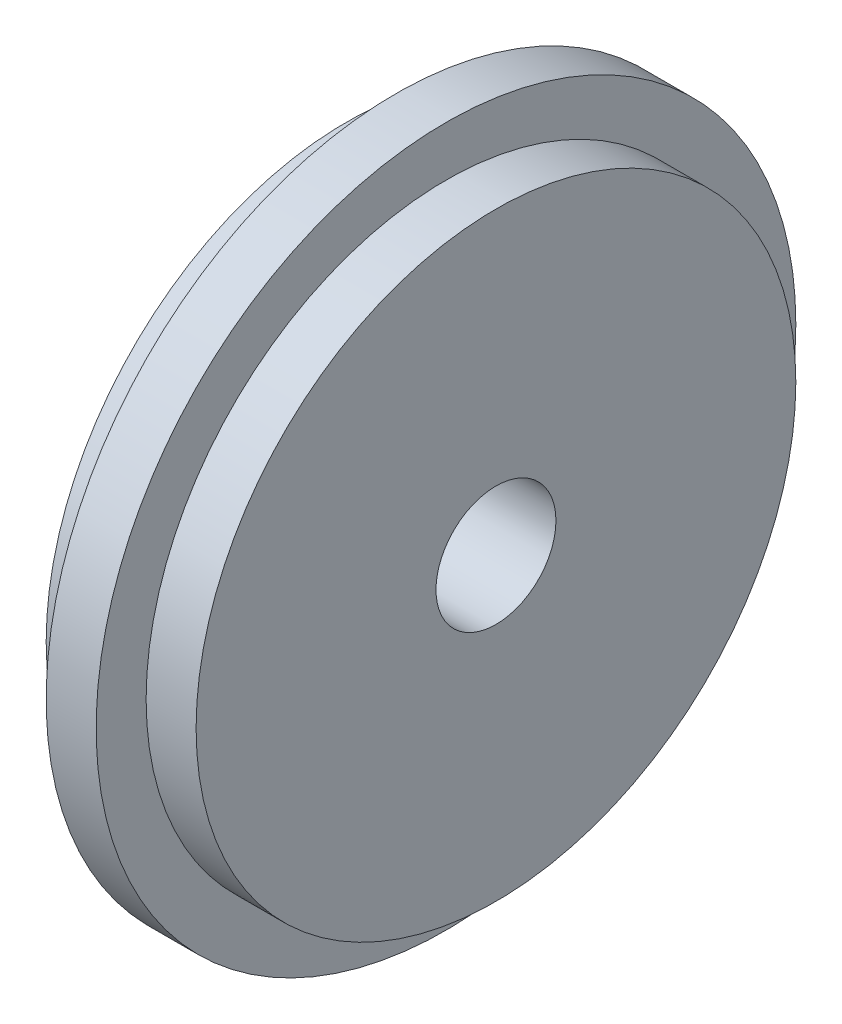
SolidWorks part; units mm, degrees
material "Náilon 6/10"
ref_plane "Plano frontal" through (0, 0, 0) normal (0, 0, 1) x (1, 0, 0)
ref_plane "Plano superior" through (0, 0, 0) normal (0, 1, 0) x (1, 0, 0)
ref_plane "Plano direito" through (0, 0, 0) normal (1, 0, 0) x (0, 0, -1)
sketch "Sketch1" plane through (0, 0, 0) normal (1, 0, 0) x (0, 0, -1)
  circle A0 centre (0, 0) radius 30
  dimension "D1" = 60
extrude "Corpo da Roda" add sketch "Sketch1" along normal mid plane 15
sketch "Sketch8" plane through (0, 0, 0) normal (1, 0, 0) x (0, 0, -1)
  circle A0 centre (0, 0) radius 35
  circle A1 centre (0, 0) radius 30 construction
  dimension "D1" = 5
extrude "Boss-Extrude2" add sketch "Sketch8" along normal mid plane 5
hole_wizard "Furo do Hub (mesmo diâmetro) - Ø1.0 (1) Diameter Hole1" positions "Sketch5" profile "Sketch4" hole size "Ø12.0" standard "DIN" end condition through all
sketch "Sketch5" plane through (7.5, 0, 0) normal (1, 0, 0) x (0, 0, -1)
  point P0 (0, 0)
sketch "Sketch4" plane through (7.5, 0, 0) normal (0, 1, 0) x (0, 0, -1)
  line L0 (0, 0) -> (0, 15)
  line L1 (0, 15) -> (6, 15)
  line L2 (6, 15) -> (6, 0)
  line L5 (6, 0) -> (0, 0)
  line L11 (0, -6.35) -> (0, 107.95) construction
  dimension "Thru Hole Dia." = 12
  dimension "Thru Hole Depth" = 15
sketch "Sketch6" plane through (0, 0, 0) normal (1, 0, 0) x (0, 0, -1)
  line L0 (0, 0) -> (0, 14) construction
  line L1 (-1.59, -9) -> (1.59, -9)
  line L2 (-1.59, -9) -> (-1.59, 2.8545)
  line L3 (-1.59, 2.8545) -> (1.59, 2.8545)
  line L4 (1.59, 2.8545) -> (1.59, -9)
  line L5 (0, 0) -> (0, -8.6042) construction
  circle A0 centre (0, 0) radius 14 construction
  circle A1 centre (0, 0) radius 6 construction
  point P10 (0, 6)
  point P11 (0, -6)
  dimension "D3" = 28
  dimension "D1" = 3
  dimension "D2" = 3.18
extrude "Rasgo de Chaveta (3.5x8x20mm)" [suppressed] cut sketch "Sketch6" against normal through all and the other way through all
hole_wizard "Furo com folga de M31" [suppressed] positions "Esboço2" profile "Esboço1" hole size "M3" standard "DIN"
sketch "Esboço2" plane through (10, 0, 0) normal (1, 0, 0) x (0, 0, -1)
  point P22 (7.2478, -7.2478)
  point P25 (7.2478, 7.2478)
  point P28 (-7.2478, 7.2478)
  point P31 (-7.2478, -7.2478)
sketch "Esboço1" plane through (10, -7.2478, -7.2478) normal (0, 1, 0) x (0, 0, -1)
  line L0 (0, 0) -> (0, 35)
  line L1 (0, 35) -> (1.7, 35)
  line L2 (1.7, 35) -> (1.7, 0)
  line L5 (1.7, 0) -> (0, 0)
  line L11 (0, -6.35) -> (0, 107.95) construction
  dimension "Thru Hole Dia." = 3.4
  dimension "Thru Hole Depth" = 35
